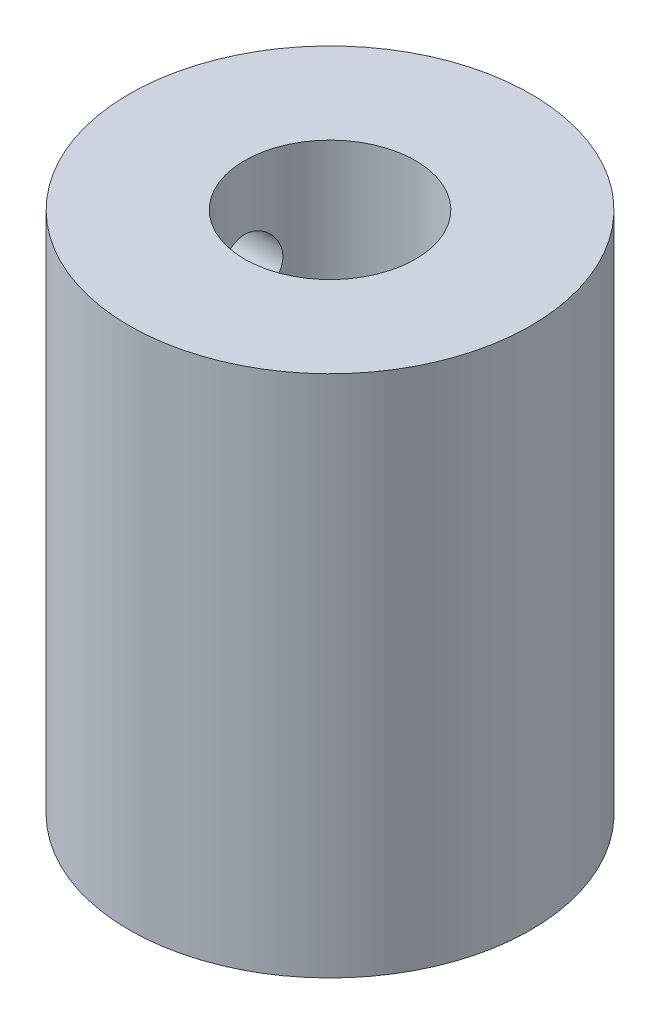
SolidWorks part; units mm, degrees
ref_plane "Front Plane" through (0, 0, 0) normal (0, 0, 1) x (1, 0, 0)
ref_plane "Top Plane" through (0, 0, 0) normal (0, 1, 0) x (1, 0, 0)
ref_plane "Right Plane" through (0, 0, 0) normal (1, 0, 0) x (0, 0, -1)
sketch "Sketch1" plane through (0, 0, 0) normal (0, 1, 0) x (1, 0, 0)
  circle A0 centre (0, 0) radius 9.4
  circle A1 centre (0, 0) radius 4
  dimension "D1" = 18.8
  dimension "D2" = 8
extrude "Boss-Extrude1" add sketch "Sketch1" along normal blind 24.5
sketch "Sketch3" plane through (0, 0, 0) normal (1, 0, 0) x (0, 0, -1)
  line L0 (-9.4, 12.25) -> (9.4, 12.25) construction
  line L1 (-9.4, 24.5) -> (-9.4, 0) construction
  line L2 (9.4, 0) -> (9.4, 24.5) construction
  circle A0 centre (0, 4.5) radius 1.5
  circle A1 centre (0, 20) radius 1.5
  dimension "D1" = 3
  dimension "D2" = 4.5
extrude "Cut-Extrude1" cut sketch "Sketch3" against normal through all
